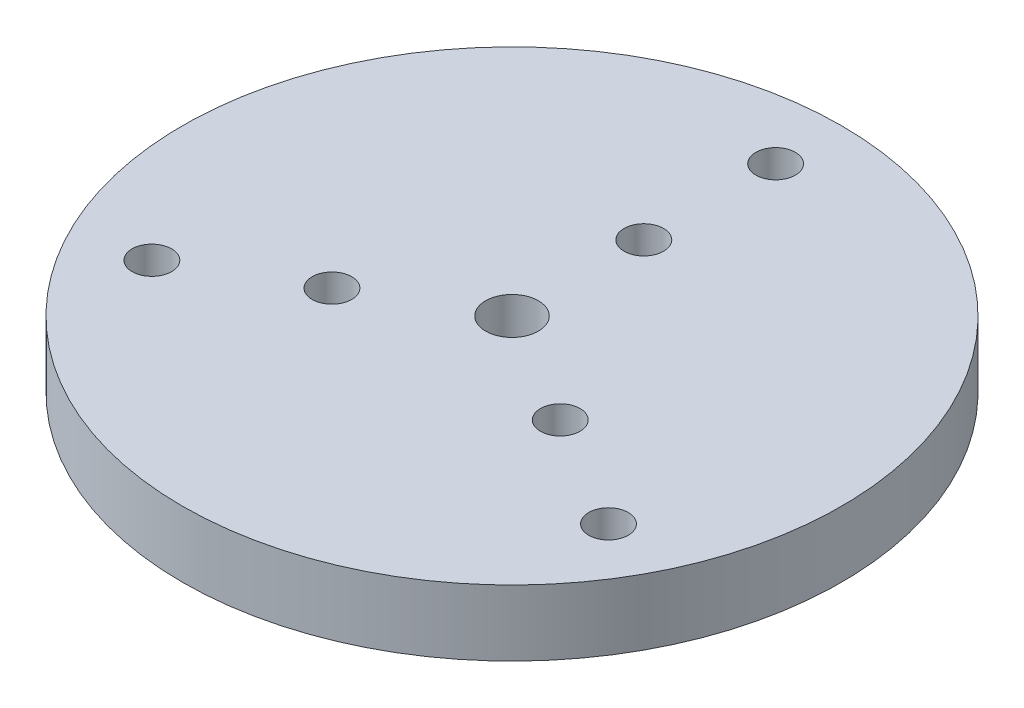
SolidWorks part; units mm, degrees
ref_plane "Front Plane" through (0, 0, 0) normal (0, 0, 1) x (1, 0, 0)
ref_plane "Top Plane" through (0, 0, 0) normal (0, 1, 0) x (1, 0, 0)
ref_plane "Right Plane" through (0, 0, 0) normal (1, 0, 0) x (0, 0, -1)
sketch "Sketch1" plane through (0, 0, 0) normal (0, 1, 0) x (1, 0, 0)
  circle A0 centre (0, 0) radius 50
  circle A1 centre (0, 0) radius 4
  circle A2 centre (0, 40) radius 3
  circle A3 centre (0, 20) radius 3
  circle A4 centre (34.641, -20) radius 3
  circle A5 centre (17.3205, -10) radius 3
  circle A6 centre (-34.641, -20) radius 3
  circle A7 centre (-17.3205, -10) radius 3
  point P19 (0, 0)
  dimension "D1" = 100
  dimension "D2" = 8
  dimension "D3" = 6
  dimension "D4" = 6
  dimension "D5" = 20
  dimension "D6" = 20
  dimension "D7" = 3
extrude "Boss-Extrude1" add sketch "Sketch1" along normal blind 10
